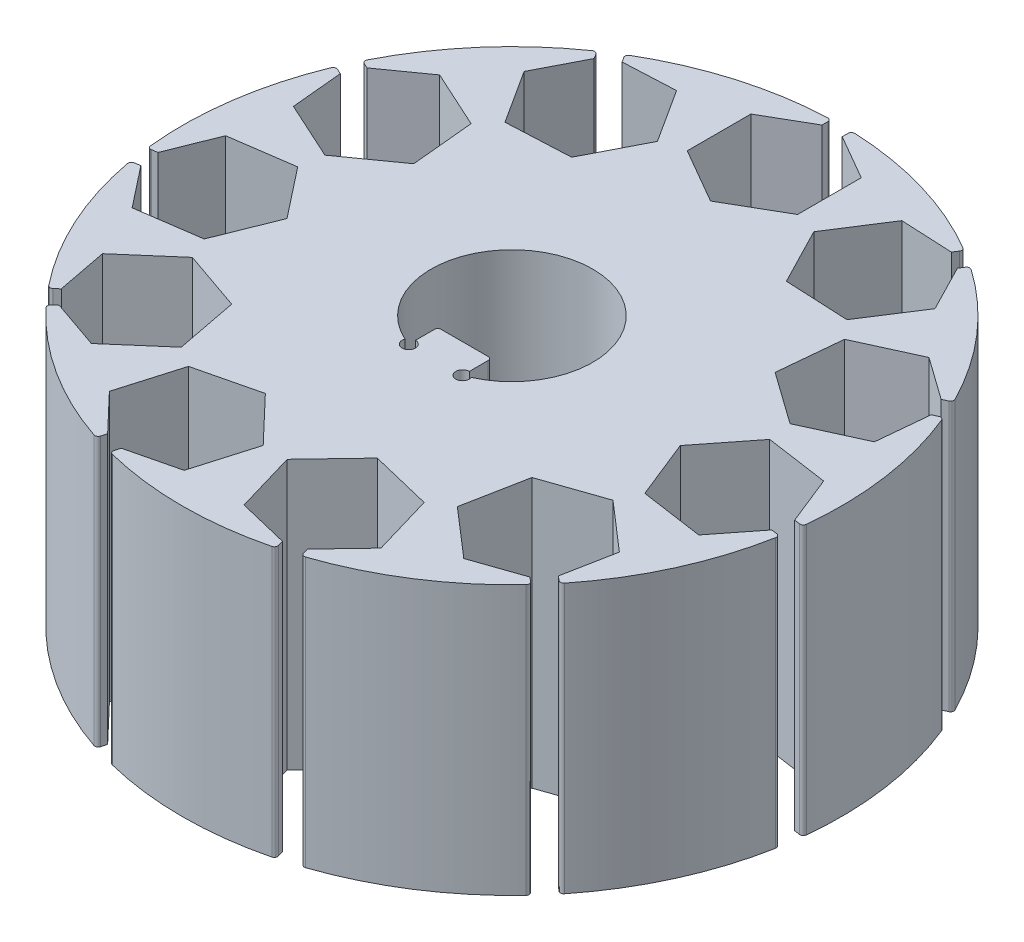
SolidWorks part; units mm, degrees
other "Markup1"
sketch "Sketch4" plane through (-24.5, 20, 24.5) normal (-0.2017, 0.9671, 0.155) x (-0.9745, -0.1822, -0.1314)
ref_plane "Front Plane" through (0, 0, 0) normal (0, 0, 1) x (1, 0, 0)
ref_plane "Top Plane" through (0, 0, 0) normal (0, 1, 0) x (1, 0, 0)
ref_plane "Right Plane" through (0, 0, 0) normal (1, 0, 0) x (0, 0, -1)
sketch "Sketch1" plane through (0, 0, 0) normal (0, 1, 0) x (1, 0, 0)
  line L0 (0, -6.01) -> (0, 0) construction
  line L12 (2, -5.1675) -> (2, -3.51)
  line L13 (2, -3.51) -> (-2, -3.51)
  line L14 (-2, -5.1675) -> (-2, -3.51)
  line L15 (2, -5.6675) -> (-2, -5.6675) construction
  circle A0 centre (0, 0) radius 24.5
  arc A6 (2.4642, -5.4816) -> (-2.4642, -5.4816) centre (0, 0) ccw
  arc A8 (-2, -5.6675) -> (2, -5.6675) centre (0, 0) ccw construction
  arc A9 (2, -5.1675) -> (2.4642, -5.4816) centre (2, -5.6675) ccw
  arc A10 (-2.4642, -5.4816) -> (-2, -5.1675) centre (-2, -5.6675) ccw
  point P3 (0, -3.51)
  point P4 (0, -6.01)
  point P6 (0, -6.01)
  point P7 (0, 24.5)
  dimension "D1" = 49
  dimension "D2" = 12.02
  dimension "D5" = 1
  dimension "D3" = 4
  dimension "D4" = 2.5
extrude "Boss-Extrude1" add sketch "Sketch1" along normal blind 20
sketch "Sketch3" plane through (0, 20, 0) normal (0, 1, 0) x (1, 0, 0)
  line L53 (0, 19.5) -> (0, 24.5) construction
  line L54 (0.75, 23.8013) -> (0.75, 24.5)
  line L55 (-0.75, 23.8013) -> (-0.75, 24.5)
  line L56 (0.75, 24.5) -> (-0.75, 24.5)
  line L58 (-4.1, 17.1329) -> (0, 14.7657)
  line L59 (0, 14.7657) -> (4.1, 17.1329)
  line L60 (4.1, 17.1329) -> (4.1, 21.8671)
  line L61 (4.1, 21.8671) -> (0.75, 23.8013)
  line L62 (-0.75, 23.8013) -> (-4.1, 21.8671)
  line L63 (-4.1, 21.8671) -> (-4.1, 17.1329)
  circle A0 centre (0, 19.5) radius 4.1 construction
  circle A3 centre (0, 0) radius 24.5 construction
  point P10 (0, 24.5)
  dimension "D2" = 5
  dimension "D3" = 1.5
  dimension "D1" = 8.2
extrude "Cut-Extrude1" cut sketch "Sketch3" against normal through all
fillet "Fillet1" radius 0.25 2 edges at (-0.75, 10, -24.4885) (0.75, 10, -24.4885)
pattern_circular "CirPattern1" count 11 over 360 about axis through (0, 0, 0) along (0, 1, 0) of "Cut-Extrude1", "Fillet1"
fillet "Fillet2" radius 0.25 2 edges at (-2, 10, 3.51) (2, 10, 3.51)
equation "\"shaft_diameter\"= 12.02"
equation "\"outerdiameter\"=49"
equation "\"numberofbars\"= 11"
equation "\"t\"= 20"
equation "\"width\"=1.5"
equation "\"bardiameter\"= 4.4"
equation "\"D1@Sketch1\"=\"outerdiameter\""
equation "\"centerdepth\"= 5"
equation "\"D1@Boss-Extrude1\"= \"t\""
equation "\"key_width\"= 4"
equation "\"key_height\"= 2.5"
equation "\"D2@Sketch3\"=\"centerdepth\""
equation "\"D3@Sketch3\"=\"width\""
equation "\"D1@CirPattern1\"=\"numberofbars\""
equation "\"RF1\"= 0.25"
equation "\"D1@Fillet1\"=\"RF1\""
equation "\"D2@Sketch1\"=\"shaft_diameter\""
equation "\"D3@Sketch1\"=\"key_width\""
equation "\"D4@Sketch1\"=\"key_height\""
